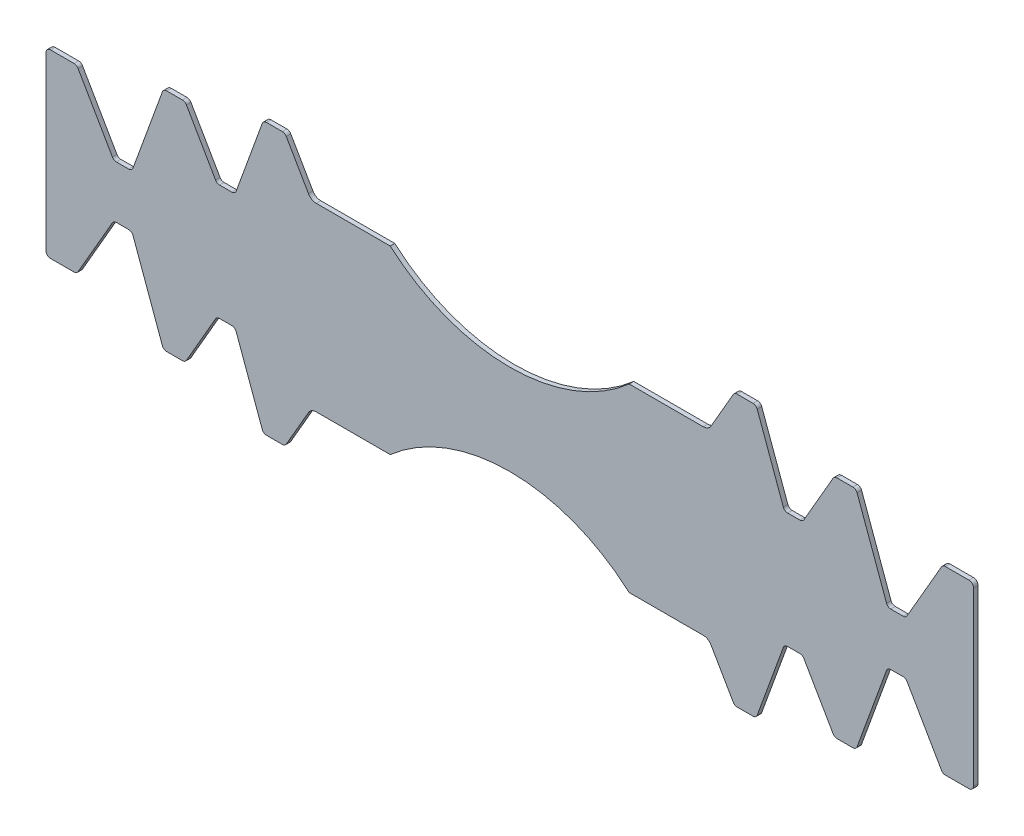
SolidWorks part; units mm, degrees
ref_plane "Front Plane" through (0, 0, 0) normal (0, 0, 1) x (1, 0, 0)
ref_plane "Top Plane" through (0, 0, 0) normal (0, 1, 0) x (1, 0, 0)
ref_plane "Right Plane" through (0, 0, 0) normal (1, 0, 0) x (0, 0, -1)
sketch "Model" plane through (0, 0, 0) normal (0, 0, 1) x (1, 0, 0)
  line L0 (1561.6044, 393.6) -> (1562.9779, 393.6)
  line L1 (1558.2438, 385.329) -> (1561.1345, 393.271)
  line L2 (1557.774, 385) -> (1556.0192, 385)
  line L3 (1555.5862, 385.25) -> (1553.1324, 389.5)
  line L4 (1552.2664, 390) -> (1544.0725, 390)
  line L5 (1509.4211, 390) -> (1517.615, 390)
  line L6 (1506.1014, 385.25) -> (1508.5551, 389.5)
  line L7 (1503.9135, 385) -> (1505.6683, 385)
  line L8 (1503.4437, 385.329) -> (1500.553, 393.271)
  line L9 (1500.0832, 393.6) -> (1498.7097, 393.6)
  line L10 (1495.0435, 387.75) -> (1498.2767, 393.35)
  line L11 (1492.8557, 387.5) -> (1494.6105, 387.5)
  line L12 (1492.3858, 387.829) -> (1489.1312, 396.771)
  line L13 (1488.6614, 397.1) -> (1487.2879, 397.1)
  line L14 (1483.0443, 390.25) -> (1486.8548, 396.85)
  line L15 (1480, 390) -> (1482.6113, 390)
  line L16 (1479.5, 390.5) -> (1479.5, 409.5)
  line L17 (1480, 410) -> (1482.6113, 410)
  line L18 (1483.0443, 409.75) -> (1486.8548, 403.15)
  line L19 (1488.6614, 402.9) -> (1487.2879, 402.9)
  line L20 (1492.3858, 412.171) -> (1489.1312, 403.229)
  line L21 (1492.8557, 412.5) -> (1494.6105, 412.5)
  line L22 (1495.0435, 412.25) -> (1498.2767, 406.65)
  line L23 (1500.0832, 406.4) -> (1498.7097, 406.4)
  line L24 (1503.4437, 414.671) -> (1500.553, 406.729)
  line L25 (1503.9135, 415) -> (1505.6683, 415)
  line L26 (1506.1014, 414.75) -> (1508.5551, 410.5)
  line L27 (1509.4211, 410) -> (1517.615, 410)
  line L28 (1552.2664, 410) -> (1544.0725, 410)
  line L29 (1555.5862, 414.75) -> (1553.1324, 410.5)
  line L30 (1557.774, 415) -> (1556.0192, 415)
  line L31 (1558.2438, 414.671) -> (1561.1345, 406.729)
  line L32 (1561.6044, 406.4) -> (1562.9779, 406.4)
  line L33 (1566.644, 412.25) -> (1563.4109, 406.65)
  line L34 (1568.8318, 412.5) -> (1567.077, 412.5)
  line L35 (1569.3017, 412.171) -> (1572.5563, 403.229)
  line L36 (1573.0262, 402.9) -> (1574.3997, 402.9)
  line L37 (1578.6432, 409.75) -> (1574.8327, 403.15)
  line L38 (1581.6875, 410) -> (1579.0762, 410)
  line L39 (1582.1875, 409.5) -> (1582.1875, 390.5)
  line L40 (1581.6875, 390) -> (1579.0762, 390)
  line L41 (1578.6432, 390.25) -> (1574.8327, 396.85)
  line L42 (1573.0262, 397.1) -> (1574.3997, 397.1)
  line L43 (1569.3017, 387.829) -> (1572.5563, 396.771)
  line L44 (1568.8318, 387.5) -> (1567.077, 387.5)
  line L45 (1566.644, 387.75) -> (1563.4109, 393.35)
  arc A0 (1561.6044, 393.6) -> (1561.1345, 393.271) centre (1561.6044, 393.1) ccw
  arc A1 (1557.774, 385) -> (1558.2438, 385.329) centre (1557.774, 385.5) ccw
  arc A2 (1555.5862, 385.25) -> (1556.0192, 385) centre (1556.0192, 385.5) ccw
  arc A3 (1553.1324, 389.5) -> (1552.2664, 390) centre (1552.2664, 389) ccw
  arc A4 (1544.0725, 390) -> (1517.615, 390) centre (1530.8438, 375) ccw
  arc A5 (1509.4211, 390) -> (1508.5551, 389.5) centre (1509.4211, 389) ccw
  arc A6 (1505.6683, 385) -> (1506.1014, 385.25) centre (1505.6683, 385.5) ccw
  arc A7 (1503.4437, 385.329) -> (1503.9135, 385) centre (1503.9135, 385.5) ccw
  arc A8 (1500.553, 393.271) -> (1500.0832, 393.6) centre (1500.0832, 393.1) ccw
  arc A9 (1498.7097, 393.6) -> (1498.2767, 393.35) centre (1498.7097, 393.1) ccw
  arc A10 (1494.6105, 387.5) -> (1495.0435, 387.75) centre (1494.6105, 388) ccw
  arc A11 (1492.3858, 387.829) -> (1492.8557, 387.5) centre (1492.8557, 388) ccw
  arc A12 (1489.1312, 396.771) -> (1488.6614, 397.1) centre (1488.6614, 396.6) ccw
  arc A13 (1487.2879, 397.1) -> (1486.8548, 396.85) centre (1487.2879, 396.6) ccw
  arc A14 (1482.6113, 390) -> (1483.0443, 390.25) centre (1482.6113, 390.5) ccw
  arc A15 (1479.5, 390.5) -> (1480, 390) centre (1480, 390.5) ccw
  arc A16 (1480, 410) -> (1479.5, 409.5) centre (1480, 409.5) ccw
  arc A17 (1483.0443, 409.75) -> (1482.6113, 410) centre (1482.6113, 409.5) ccw
  arc A18 (1486.8548, 403.15) -> (1487.2879, 402.9) centre (1487.2879, 403.4) ccw
  arc A19 (1488.6614, 402.9) -> (1489.1312, 403.229) centre (1488.6614, 403.4) ccw
  arc A20 (1492.8557, 412.5) -> (1492.3858, 412.171) centre (1492.8557, 412) ccw
  arc A21 (1495.0435, 412.25) -> (1494.6105, 412.5) centre (1494.6105, 412) ccw
  arc A22 (1498.2767, 406.65) -> (1498.7097, 406.4) centre (1498.7097, 406.9) ccw
  arc A23 (1500.0832, 406.4) -> (1500.553, 406.729) centre (1500.0832, 406.9) ccw
  arc A24 (1503.9135, 415) -> (1503.4437, 414.671) centre (1503.9135, 414.5) ccw
  arc A25 (1506.1014, 414.75) -> (1505.6683, 415) centre (1505.6683, 414.5) ccw
  arc A26 (1508.5551, 410.5) -> (1509.4211, 410) centre (1509.4211, 411) ccw
  arc A27 (1517.615, 410) -> (1544.0725, 410) centre (1530.8438, 425) ccw
  arc A28 (1552.2664, 410) -> (1553.1324, 410.5) centre (1552.2664, 411) ccw
  arc A29 (1556.0192, 415) -> (1555.5862, 414.75) centre (1556.0192, 414.5) ccw
  arc A30 (1558.2438, 414.671) -> (1557.774, 415) centre (1557.774, 414.5) ccw
  arc A31 (1561.1345, 406.729) -> (1561.6044, 406.4) centre (1561.6044, 406.9) ccw
  arc A32 (1562.9779, 406.4) -> (1563.4109, 406.65) centre (1562.9779, 406.9) ccw
  arc A33 (1567.077, 412.5) -> (1566.644, 412.25) centre (1567.077, 412) ccw
  arc A34 (1569.3017, 412.171) -> (1568.8318, 412.5) centre (1568.8318, 412) ccw
  arc A35 (1572.5563, 403.229) -> (1573.0262, 402.9) centre (1573.0262, 403.4) ccw
  arc A36 (1574.3997, 402.9) -> (1574.8327, 403.15) centre (1574.3997, 403.4) ccw
  arc A37 (1579.0762, 410) -> (1578.6432, 409.75) centre (1579.0762, 409.5) ccw
  arc A38 (1582.1875, 409.5) -> (1581.6875, 410) centre (1581.6875, 409.5) ccw
  arc A39 (1581.6875, 390) -> (1582.1875, 390.5) centre (1581.6875, 390.5) ccw
  arc A40 (1578.6432, 390.25) -> (1579.0762, 390) centre (1579.0762, 390.5) ccw
  arc A41 (1574.8327, 396.85) -> (1574.3997, 397.1) centre (1574.3997, 396.6) ccw
  arc A42 (1573.0262, 397.1) -> (1572.5563, 396.771) centre (1573.0262, 396.6) ccw
  arc A43 (1568.8318, 387.5) -> (1569.3017, 387.829) centre (1568.8318, 388) ccw
  arc A44 (1566.644, 387.75) -> (1567.077, 387.5) centre (1567.077, 388) ccw
  arc A45 (1563.4109, 393.35) -> (1562.9779, 393.6) centre (1562.9779, 393.1) ccw
extrude "Boss-Extrude1" add sketch "Model" along normal blind 0.5 contours L24 A23 L23 A22 L22 A21 L21 A20 L20 A19 L19 A18 L18 A17 L17 A16 L16 A15 L15 A14 L14 A13 L13 A12 L12 A11 L11 A10 L10 A9 L9 A8 L8 A7 L7 A6 L6 A5 L5 A4 L4 A3 L3 A2 L2 A1 L1 A0 L0 A45 L45 A44 L44 A43 L43 A42 L42 A41 L41 A40 L40 A39 L39 A38 L38 A37 L37 A36 L36 A35 L35 A34 L34 A33 L33 A32 L32 A31 L31 A30 L30 A29 L29 A28 L28 A27 L27 A26 L26 A25 L25 A24
